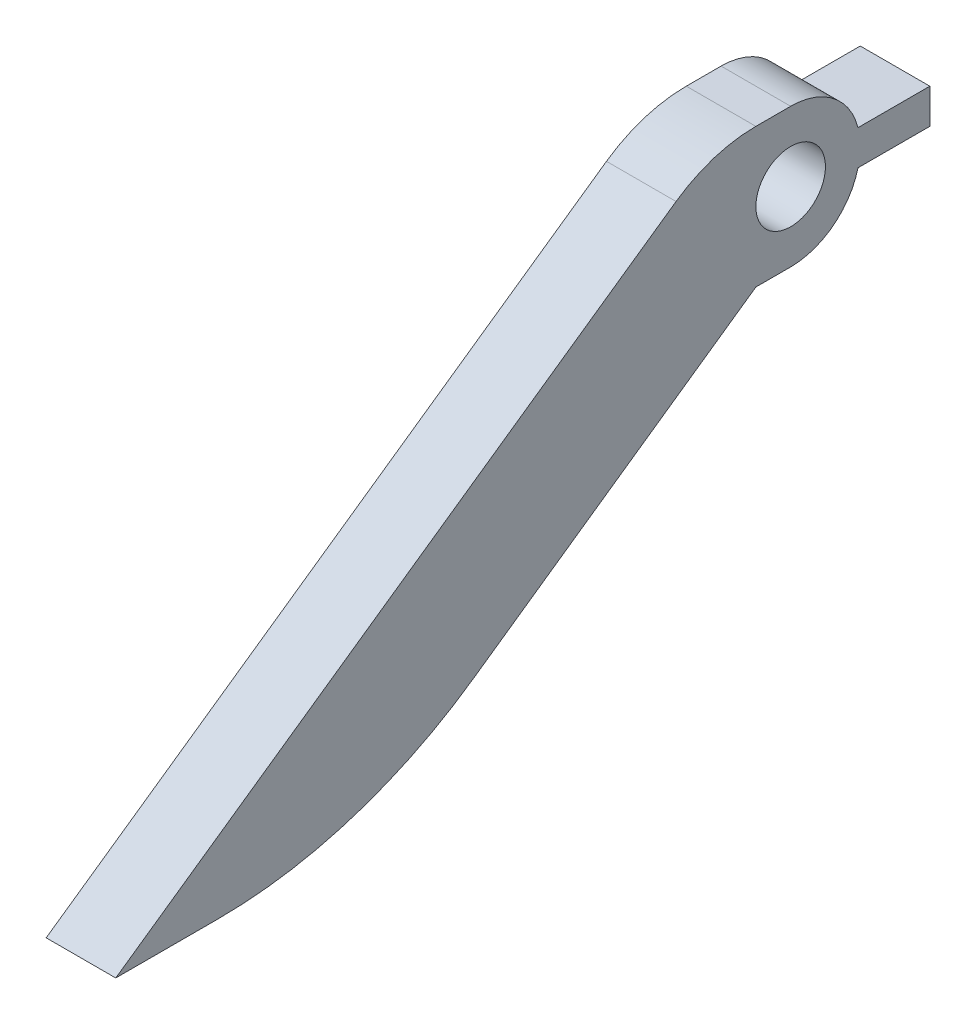
SolidWorks part; units mm, degrees
material "PE High Density"
ref_plane "Front Plane" through (0, 0, 0) normal (0, 0, 1) x (1, 0, 0)
ref_plane "Top Plane" through (0, 0, 0) normal (0, 1, 0) x (1, 0, 0)
ref_plane "Right Plane" through (0, 0, 0) normal (1, 0, 0) x (0, 0, -1)
sketch "Sketch2" plane through (0, 0, 0) normal (1, 0, 0) x (0, 0, -1)
  line L0 (-11.0709, 0) -> (11.0709, 0)
  line L1 (-11.0709, 0) -> (40.0614, 35.8032)
  line L2 (11.0709, 0) -> (47.3458, 25.4)
  line L5 (0, 0) -> (21.9556, 0) construction
  line L6 (47.3458, 38.1) -> (50.5208, 38.1)
  line L7 (47.3458, 38.1) -> (47.3458, 25.4) construction
  line L8 (47.3458, 25.4) -> (50.5208, 25.4)
  line L12 (56.6692, 33.3375) -> (63.2208, 33.3375)
  line L13 (63.2208, 33.3375) -> (63.2208, 30.1625)
  line L14 (63.2208, 30.1625) -> (56.6692, 30.1625)
  arc A0 (50.5208, 25.4) -> (50.5208, 38.1) centre (50.5208, 31.75) ccw
  arc A1 (40.0614, 35.8032) -> (47.3458, 38.1) centre (47.3458, 25.4) cw
  circle A2 centre (50.5208, 31.75) radius 3.175
  point P4 (0, 0)
  point P16 (63.2208, 31.75)
  point P18 (56.8708, 31.75)
  dimension "D1" = 6.35
  dimension "D6" = 6.35
  dimension "D2" = 12.7
  dimension "D3" = 35
  dimension "D4" = 3.175
  dimension "D5" = 31.75
  dimension "D7" = 6.35
  dimension "D8" = 3.175
extrude "Boss-Extrude1" add sketch "Sketch2" along normal blind 6.35 contours A1 L1 L0 L2 L8 A0 L6 A2 | A0 L14 L13 L12
fillet "Fillet1" radius 40.64 1 edges at (3.175, 0, -11.0709)
